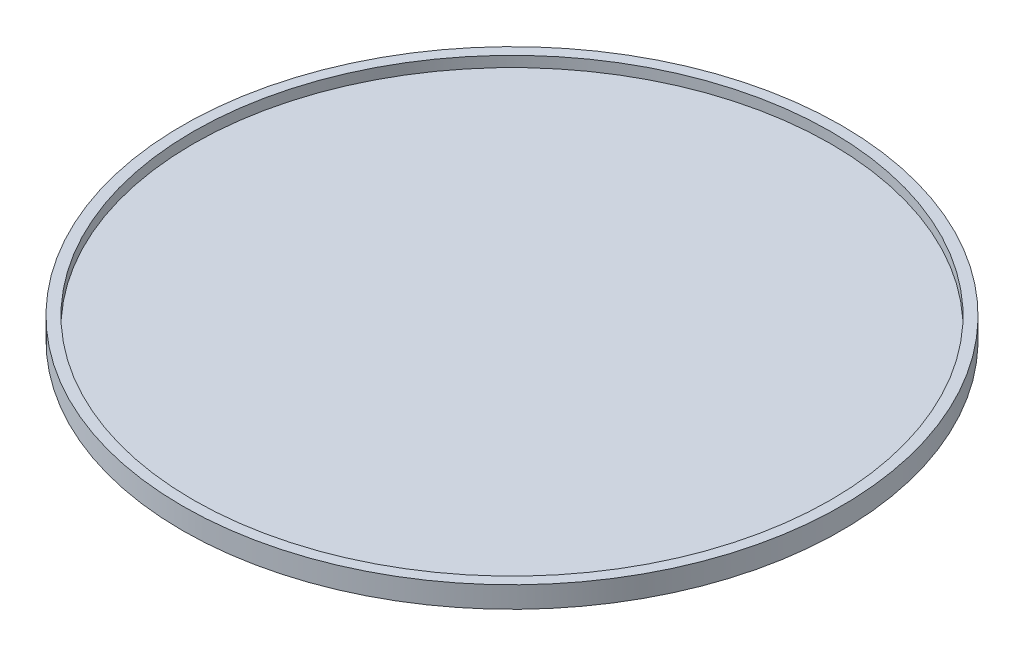
SolidWorks part; units mm, degrees
ref_plane "Front Plane" through (0, 0, 0) normal (0, 0, 1) x (1, 0, 0)
ref_plane "Top Plane" through (0, 0, 0) normal (0, 1, 0) x (1, 0, 0)
ref_plane "Right Plane" through (0, 0, 0) normal (1, 0, 0) x (0, 0, -1)
sketch "Sketch1" plane through (0, 0, 0) normal (0, 1, 0) x (1, 0, 0)
  circle A0 centre (0, 0) radius 155
  dimension "D1" = 310
extrude "Boss-Extrude1" add sketch "Sketch1" along normal blind 5
sketch "Sketch2" plane through (0, 5, 0) normal (0, 1, 0) x (1, 0, 0)
  circle A0 centre (0, 0) radius 150
  circle A1 centre (0, 0) radius 155
  dimension "D1" = 300
extrude "Boss-Extrude2" add sketch "Sketch2" along normal blind 5
